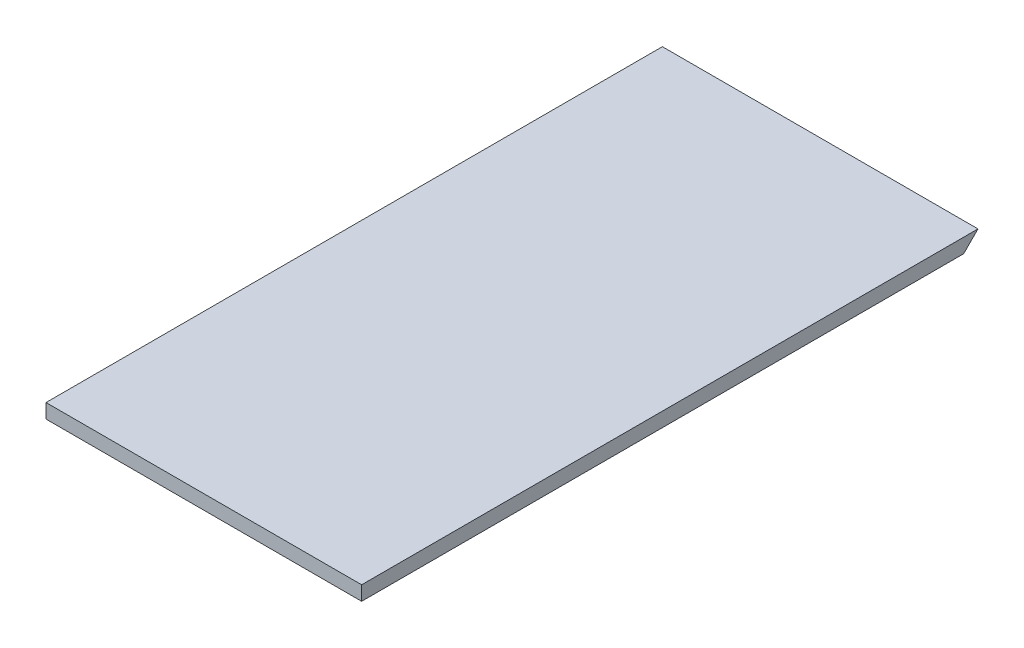
SolidWorks part; units mm, degrees
ref_plane "Front Plane" through (0, 0, 0) normal (0, 0, 1) x (1, 0, 0)
ref_plane "Top Plane" through (0, 0, 0) normal (0, 1, 0) x (1, 0, 0)
ref_plane "Right Plane" through (0, 0, 0) normal (1, 0, 0) x (0, 0, -1)
sketch "Sketch1" plane through (0, 0, 0) normal (1, 0, 0) x (0, 0, -1)
  line L0 (0, 0) -> (0, 12.7)
  line L1 (0, 12.7) -> (545.592, 12.7)
  line L2 (0, 0) -> (532.892, 0)
  line L3 (532.892, 0) -> (545.592, 12.7)
  dimension "D1" = 545.592
  dimension "D2" = 532.892
  dimension "D3" = 12.7
extrude "Boss-Extrude1" add sketch "Sketch1" along normal blind 279.4
